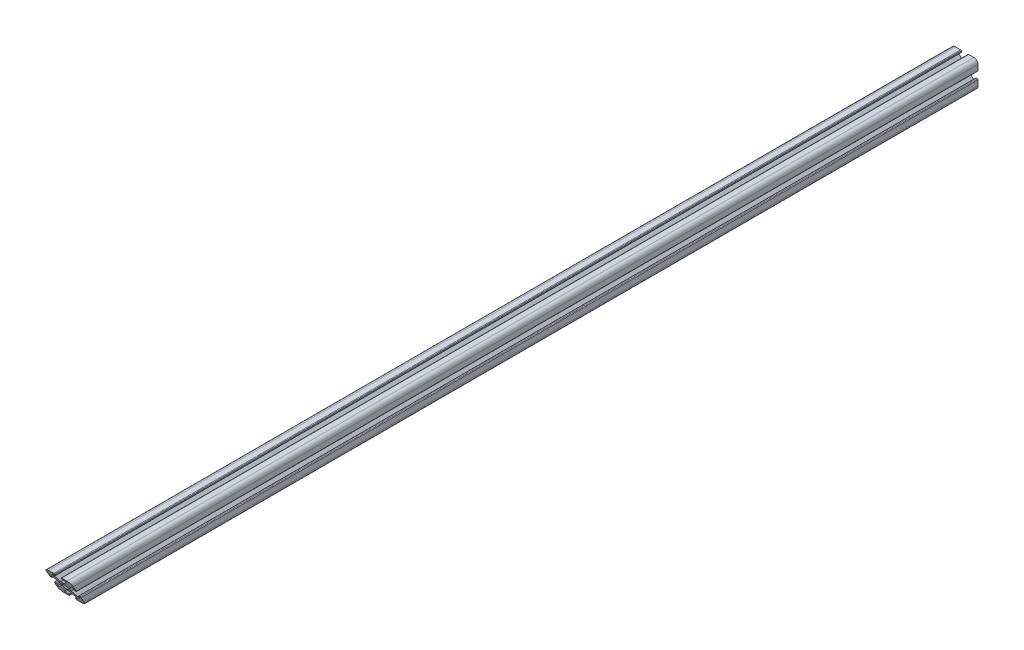
SolidWorks part; units mm, degrees
ref_plane "Front Plane" through (0, 0, 0) normal (0, 0, 1) x (1, 0, 0)
ref_plane "Top Plane" through (0, 0, 0) normal (0, 1, 0) x (1, 0, 0)
ref_plane "Right Plane" through (0, 0, 0) normal (1, 0, 0) x (0, 0, -1)
sketch "Sketch1" plane through (0, 0, 0) normal (0, 0, 1) x (1, 0, 0)
  line L1 (-3.65, 3.65) -> (3.65, 3.65)
  line L2 (-3.65, 3.65) -> (-3.65, -3.65)
  line L3 (-3.65, -3.65) -> (3.65, -3.65)
  line L4 (3.65, 3.65) -> (3.65, -3.65)
  line L5 (-3.65, 3.65) -> (3.65, -3.65) construction
  line L6 (-3.65, -3.65) -> (3.65, 3.65) construction
  circle A0 centre (0, 0) radius 2.15
  point P0 (0, 0)
  dimension "D1" = 7.3
  dimension "D2" = 7.3
extrude "Boss-Extrude1" add sketch "Sketch1" along normal blind 680
sketch "Sketch2" plane through (0, 0, 0) normal (0, 0, 1) x (1, 0, 0)
  line L0 (3.65, 3.65) -> (1.2, 3.65)
  line L1 (3.65, 3.65) -> (-3.65, 3.65) construction
  line L2 (3.65, -3.65) -> (3.65, 3.65) construction
  line L4 (3.65, 3.65) -> (3.65, 1.2)
  line L5 (1.2, 3.65) -> (5.75, 8.2)
  line L6 (3.65, 1.2) -> (8.2, 5.75)
  line L7 (8.2, 5.75) -> (8.2, 2.5)
  line L8 (5.75, 8.2) -> (2.5, 8.2)
  line L9 (8.2, 2.5) -> (10, 2.5)
  line L10 (2.5, 8.2) -> (2.5, 10)
  line L11 (2.5, 10) -> (10, 10)
  line L12 (10, 2.5) -> (10, 10)
  line L13 (-3.65, 3.65) -> (-1.2, 3.65)
  line L14 (-3.65, 3.65) -> (-3.65, 1.2)
  line L15 (-3.65, 3.65) -> (-3.65, -3.65) construction
  line L16 (-3.65, -3.65) -> (-3.65, -1.2)
  line L17 (-3.65, -3.65) -> (-1.2, -3.65)
  line L18 (-3.65, -3.65) -> (3.65, -3.65) construction
  line L19 (3.65, -3.65) -> (3.65, -1.2)
  line L20 (3.65, -3.65) -> (1.2, -3.65)
  line L21 (-3.65, -1.2) -> (-8.2, -5.75)
  line L22 (-1.2, -3.65) -> (-5.75, -8.2)
  line L23 (3.65, -1.2) -> (8.2, -5.75)
  line L24 (1.2, -3.65) -> (5.75, -8.2)
  line L25 (-1.2, 3.65) -> (-5.75, 8.2)
  line L26 (-3.65, 1.2) -> (-8.2, 5.75)
  line L27 (-5.75, 8.2) -> (-2.5, 8.2)
  line L28 (-8.2, 5.75) -> (-8.2, 2.5)
  line L29 (8.2, -5.75) -> (8.2, -2.5)
  line L30 (5.75, -8.2) -> (2.5, -8.2)
  line L31 (-5.75, -8.2) -> (-2.5, -8.2)
  line L32 (-8.2, -5.75) -> (-8.2, -2.5)
  line L33 (8.2, -2.5) -> (10, -2.5)
  line L34 (2.5, -8.2) -> (2.5, -10)
  line L35 (-2.5, -8.2) -> (-2.5, -10)
  line L36 (-8.2, -2.5) -> (-10, -2.5)
  line L37 (-8.2, 2.5) -> (-10, 2.5)
  line L38 (-2.5, 8.2) -> (-2.5, 10)
  line L39 (-2.5, 10) -> (-10, 10)
  line L40 (-10, 10) -> (-10, 2.5)
  line L41 (-10, -2.5) -> (-10, -10)
  line L42 (-10, -10) -> (-2.5, -10)
  line L43 (2.5, -10) -> (10, -10)
  line L44 (10, -10) -> (10, -2.5)
extrude "Boss-Extrude2" add sketch "Sketch2" along normal blind 680
fillet "Fillet4" radius 3 4 edges at (-10, -10, 340) (-10, 10, 340) (10, 10, 340) (10, -10, 340)
fillet "Fillet5" radius 0.5 15 edges at (2.5, 10, 340) (2.5, 8.2, 340) (-2.5, 10, 340) (-2.5, 8.2, 340) (8.2, 2.5, 340) (-8.2, 2.5, 340) (10, 2.5, 340) (-8.2, -2.5, 340) (-2.5, -10, 340) (-2.5, -8.2, 340) (-10, 2.5, 340) (-10, -2.5, 340) (10, -2.5, 340) (8.2, -2.5, 340) (2.5, -8.2, 340)
fillet "Fillet6" radius 0.5 8 edges at (1.2, -3.65, 340) (-1.2, -3.65, 340) (3.65, -1.2, 340) (3.65, 1.2, 340) (-1.2, 3.65, 340) (1.2, 3.65, 340) (-3.65, -1.2, 340) (-3.65, 1.2, 340)
fillet "Fillet7" radius 0.5 8 edges at (8.2, -5.75, 340) (8.2, 5.75, 340) (-8.2, -5.75, 340) (5.75, 8.2, 340) (-5.75, -8.2, 340) (5.75, -8.2, 340) (-8.2, 5.75, 340) (-5.75, 8.2, 340)
sketch "Sketch3" plane through (0, 0, 0) normal (1, 0, 0) x (0, 0, -1)
  line L0 (-680, 10) -> (-680, -10)
  line L1 (-680, -10) -> (-668.453, -10)
  line L2 (-680, 10) -> (-668.453, -10)
  dimension "D1" = 11.547
extrude "Cut-Extrude1" cut sketch "Sketch3" against normal through all
sketch "Sketch4" plane through (0, 0, 0) normal (1, 0, 0) x (0, 0, -1)
  line L0 (-680, 10) -> (-680, -10)
  line L1 (-680, -10) -> (-668.453, -10)
  line L2 (-668.453, -10) -> (-680, 10)
extrude "Cut-Extrude5" cut sketch "Sketch4" along normal through all
sketch "Sketch5" plane through (-3.65, 0, 0) normal (-1, 0, 0) x (0, 0, 1)
  line L0 (674.2265, 0) -> (659.2265, 0) construction
  line L1 (673.6533, -0.9929) -> (674.7997, 0.9929) construction
  circle A0 centre (659.2265, 0) radius 2.15
  dimension "D1" = 15
extrude "Cut-Extrude6" cut sketch "Sketch5" against normal through all
sketch "Sketch6" plane through (3.65, 0, 0) normal (1, 0, 0) x (0, 0, -1)
  line L0 (-674.2265, 0) -> (-659.2265, 0) construction
  line L1 (-673.6533, -0.9929) -> (-674.7997, 0.9929) construction
  circle A0 centre (-659.2265, 0) radius 2.15
  dimension "D1" = 15
extrude "Cut-Extrude7" cut sketch "Sketch6" against normal through all
sketch "Sketch9" plane through (3.65, 0, 0) normal (1, 0, 0) x (0, 0, -1)
  line L0 (0, 0) -> (-50.8, 0) construction
  circle A0 centre (-50.8, 0) radius 2.15
  dimension "D1" = 50.8
extrude "Cut-Extrude10" cut sketch "Sketch9" against normal through all
sketch "Sketch10" plane through (-3.65, 0, 0) normal (-1, 0, 0) x (0, 0, 1)
  line L0 (0, 0) -> (50.8, 0) construction
  circle A0 centre (50.8, 0) radius 2.15
  dimension "D1" = 50.8
extrude "Cut-Extrude11" cut sketch "Sketch10" against normal through all
sketch "Sketch13" plane through (3.65, 0, 0) normal (1, 0, 0) x (0, 0, -1)
  line L0 (0, 0) -> (-20, 0) construction
  line L2 (0, -0.9929) -> (0, 0.9929) construction
  circle A0 centre (-20, 0) radius 2.15
  dimension "D1" = 20
extrude "Cut-Extrude14" cut sketch "Sketch13" against normal through all
sketch "Sketch14" plane through (-3.65, 0, 0) normal (-1, 0, 0) x (0, 0, 1)
  line L0 (0, 0) -> (20, 0) construction
  circle A0 centre (20, 0) radius 2.15
extrude "Cut-Extrude15" cut sketch "Sketch14" against normal through all
